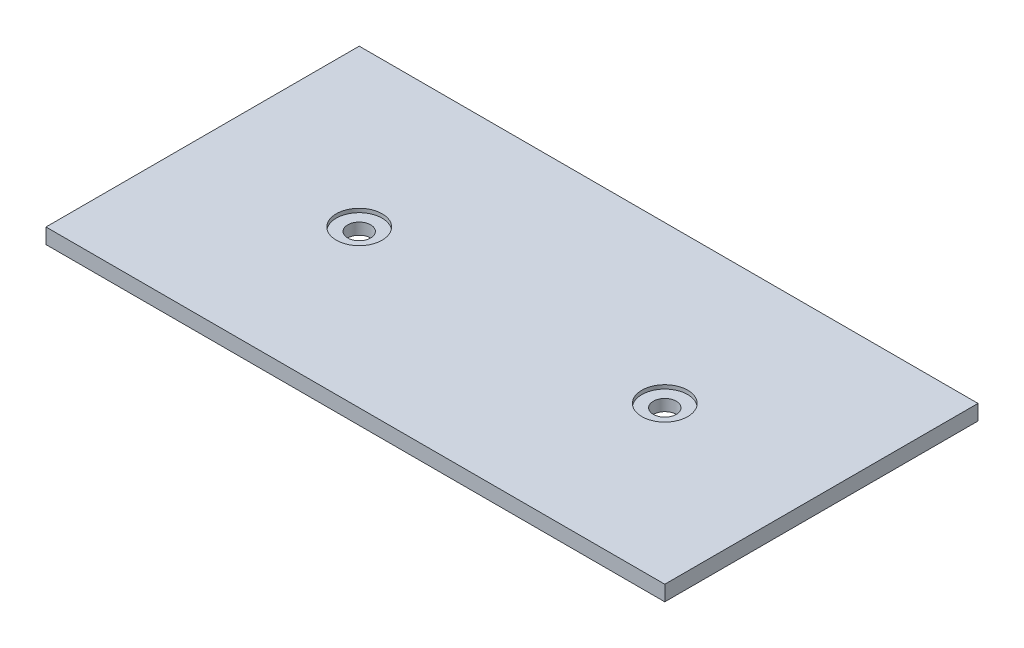
SolidWorks part; units mm, degrees
ref_plane "Front" through (0, 0, 0) normal (0, 0, 1) x (1, 0, 0)
ref_plane "Top" through (0, 0, 0) normal (0, 1, 0) x (1, 0, 0)
ref_plane "Right" through (0, 0, 0) normal (1, 0, 0) x (0, 0, -1)
sketch "Sketch1" plane through (0, 0, 0) normal (0, 1, 0) x (1, 0, 0)
  line L1 (0, 0) -> (81, 0)
  line L2 (0, 0) -> (0, 41)
  line L3 (0, 41) -> (81, 41)
  line L4 (81, 0) -> (81, 41)
  dimension "D1" = 81
  dimension "D2" = 41
extrude "Boss-Extrude1" add sketch "Sketch1" along normal blind 2
sketch "Sketch2" plane through (0, 2, 0) normal (0, 1, 0) x (1, 0, 0)
  line L0 (81, 41) -> (0, 41) construction
  line L1 (0, 41) -> (0, 0) construction
  line L2 (81, 0) -> (81, 41) construction
  line L3 (0, 0) -> (81, 0) construction
  circle A0 centre (20.5, 20.5) radius 3
  circle A1 centre (60.5, 20.5) radius 3
  dimension "D1" = 20.5
  dimension "D5" = 6
  dimension "D6" = 6
  dimension "D2" = 20.5
  dimension "D3" = 20.5
  dimension "D4" = 20.5
extrude "Cut-Extrude1" cut sketch "Sketch2" against normal blind 0.5
sketch "Sketch3" plane through (0, 1.5, 0) normal (0, 1, 0) x (1, 0, 0)
  circle A0 centre (20.5, 20.5) radius 1.5
  circle A1 centre (60.5, 20.5) radius 1.5
  dimension "D1" = 3
  dimension "D2" = 3
extrude "Cut-Extrude2" cut sketch "Sketch3" against normal through all
sketch "Sketch4" plane through (0, 0, 0) normal (0, -1, 0) x (1, 0, 0)
  line L0 (81, -41) -> (0, -41) construction
  line L1 (81, 0) -> (81, -41) construction
  circle A0 centre (70.5, -30.5) radius 3
  circle A1 centre (50.5, -30.5) radius 3
  circle A2 centre (30.5, -30.5) radius 3
  circle A3 centre (10.5, -30.5) radius 3
  circle A4 centre (50.5, -10.5) radius 3
  circle A5 centre (30.5, -10.5) radius 3
  circle A6 centre (10.5, -10.5) radius 3
  circle A7 centre (70.5, -10.5) radius 3
  dimension "D3" = 6
  dimension "D1" = 10.5
  dimension "D2" = 10.5
  dimension "D4" = 4
  dimension "D5" = 2
extrude "Boss-Extrude2" add sketch "Sketch4" along normal blind 2
